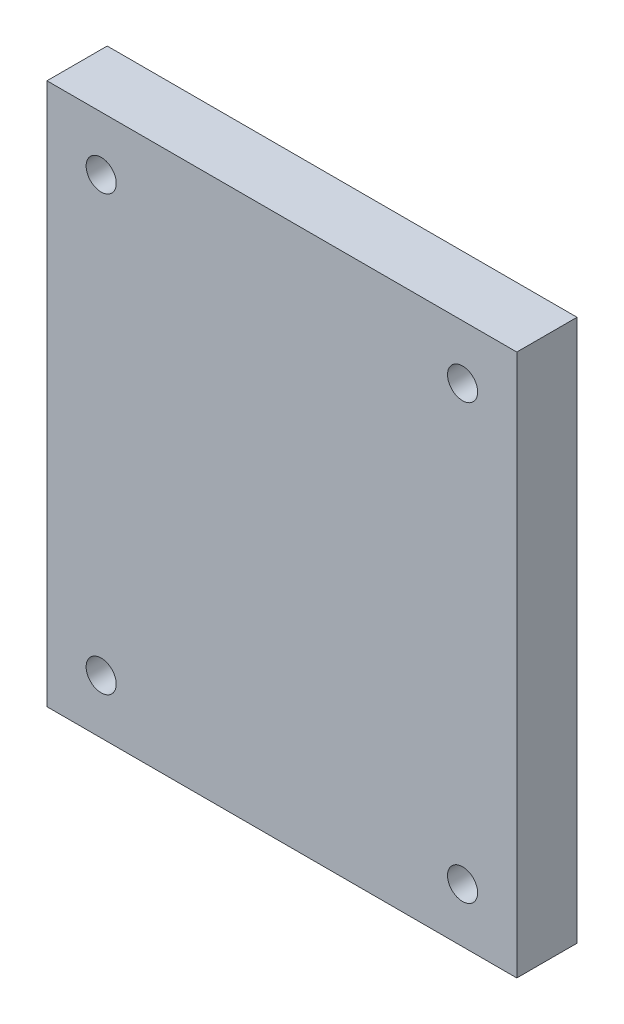
SolidWorks part; units mm, degrees
ref_plane "Front Plane" through (0, 0, 0) normal (0, 0, 1) x (1, 0, 0)
ref_plane "Top Plane" through (0, 0, 0) normal (0, 1, 0) x (1, 0, 0)
ref_plane "Right Plane" through (0, 0, 0) normal (1, 0, 0) x (0, 0, -1)
sketch "Sketch1" plane through (0, 0, 0) normal (0, 0, 1) x (1, 0, 0)
  line L0 (0, -1000) -> (0, 49000) construction
  line L1 (-19.5, 22.5) -> (19.5, 22.5)
  line L2 (-19.5, 22.5) -> (-19.5, -22.5)
  line L3 (-19.5, -22.5) -> (19.5, -22.5)
  line L4 (19.5, 22.5) -> (19.5, -22.5)
  line L5 (-1000, 0) -> (49000, 0) construction
  circle A0 centre (-15, 18) radius 1.25
  circle A1 centre (15, 18) radius 1.25
  circle A2 centre (15, -18) radius 1.25
  circle A3 centre (-15, -18) radius 1.25
  dimension "D1" = 2.5
extrude "Boss-Extrude1" add sketch "Sketch1" along normal blind 5 contours L4 L1 L2 L3 A1 A0 A2 A3
